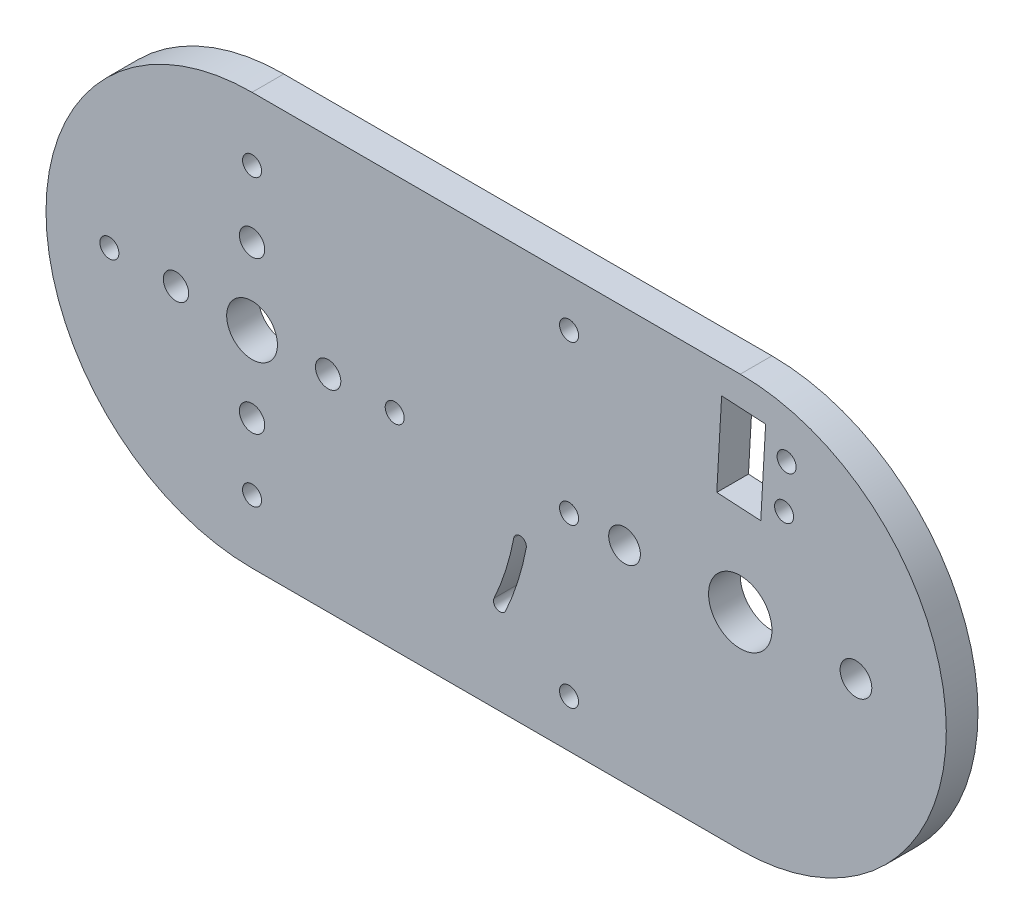
SolidWorks part; units mm, degrees
ref_plane "Front Plane" through (0, 0, 0) normal (0, 0, 1) x (1, 0, 0)
ref_plane "Top Plane" through (0, 0, 0) normal (0, 1, 0) x (1, 0, 0)
ref_plane "Right Plane" through (0, 0, 0) normal (1, 0, 0) x (0, 0, -1)
sketch "Sketch1" plane through (0, 0, 0) normal (0, 0, 1) x (1, 0, 0)
  line L0 (-38.5, 0) -> (38.5, 0) construction
  line L2 (-38.5, 32.5) -> (38.5, 32.5)
  line L3 (-38.5, -32.5) -> (38.5, -32.5)
  line L7 (42.5031, 27.6818) -> (41.7358, 14.1034)
  line L10 (42.5031, 27.6818) -> (35.5642, 28.0739)
  line L11 (35.5642, 28.0739) -> (34.7968, 14.4955)
  line L12 (34.7968, 14.4955) -> (41.7358, 14.1034)
  arc A0 (-38.5, 32.5) -> (-38.5, -32.5) centre (-38.5, 0) ccw
  arc A1 (38.5, -32.5) -> (38.5, 32.5) centre (38.5, 0) ccw
  circle A2 centre (-38.5, 0) radius 4
  circle A3 centre (38.5, 0) radius 5
  circle A4 centre (20.25, 0) radius 2.5
  circle A5 centre (56.75, 0) radius 2.5
  circle A6 centre (-38.5, -12) radius 2
  circle A7 centre (-26.5, 0) radius 2
  circle A8 centre (-38.5, 12) radius 2
  circle A9 centre (-50.5, 0) radius 2
  circle A11 centre (-38.5, 22.5) radius 1.5
  circle A12 centre (-16, 0) radius 1.5
  circle A13 centre (-38.5, -22.5) radius 1.5
  circle A14 centre (-61, 0) radius 1.5
  circle A16 centre (11.5, 0) radius 1.5
  circle A17 centre (11.5, -25) radius 1.5
  circle A19 centre (11.5, 25) radius 1.5
  arc A22 (-0.3203, -17.5017) -> (1.4978, -18.3351) centre (0.5888, -17.9184) ccw
  arc A23 (2.7802, -7.7423) -> (4.7459, -8.111) centre (3.7631, -7.9267) cw
  arc A24 (-0.3203, -17.5017) -> (2.7802, -7.7423) centre (-38.5, 0) ccw
  arc A25 (1.4978, -18.3351) -> (4.7459, -8.111) centre (-38.5, 0) ccw
  circle A26 centre (45.8113, 24.1896) radius 1.5
  circle A27 centre (45.4164, 17.2007) radius 1.5
  point P5 (0, 0)
  dimension "D3" = 18.25
  dimension "D5" = 5
  dimension "D6" = 5
  dimension "D7" = 10
  dimension "D8" = 8
  dimension "D9" = 12
  dimension "D13" = 4
  dimension "D14" = 4
  dimension "D15" = 4
  dimension "D16" = 4
  dimension "D17" = 22.5
  dimension "D21" = 3
  dimension "D22" = 3
  dimension "D23" = 3
  dimension "D24" = 3
  dimension "D25" = 27
  dimension "D26" = 7.5
  dimension "D27" = 3
  dimension "D28" = 3
  dimension "D29" = 7.5
  dimension "D30" = 3
  dimension "D31" = 3
  dimension "D32" = 3
  dimension "D33" = 1
  dimension "D34" = 1
  dimension "D36" = 7
  dimension "D1" = 77
  dimension "D2" = 65
  dimension "D4" = 18.25
  dimension "D10" = 12
  dimension "D11" = 12
  dimension "D12" = 12
  dimension "D18" = 22.5
  dimension "D19" = 22.5
  dimension "D20" = 22.5
  dimension "D35" = 10.24
  dimension "D37" = 3.5
  dimension "D38" = 6.95
  dimension "D39" = 13.6
extrude "Boss-Extrude1" add sketch "Sketch1" along normal blind 5
